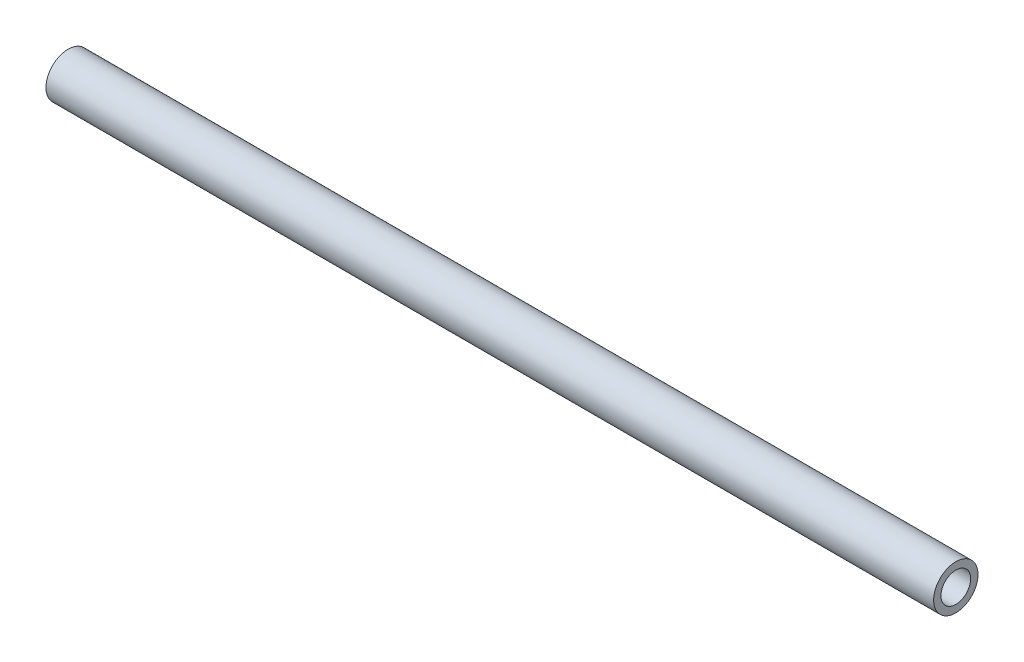
SolidWorks part; units mm, degrees
material "Nylon 101"
ref_plane "Front Plane" through (0, 0, 0) normal (0, 0, 1) x (1, 0, 0)
ref_plane "Top Plane" through (0, 0, 0) normal (0, 1, 0) x (1, 0, 0)
ref_plane "Right Plane" through (0, 0, 0) normal (1, 0, 0) x (0, 0, -1)
sketch "Sketch1" plane through (0, 0, 0) normal (1, 0, 0) x (0, 0, -1)
  circle A0 centre (0, 0) radius 3.175
  circle A1 centre (0, 0) radius 2.1273
  dimension "D1" = 6.35
  dimension "D2" = 4.2545
extrude "Boss-Extrude1" add sketch "Sketch1" along normal blind 127
